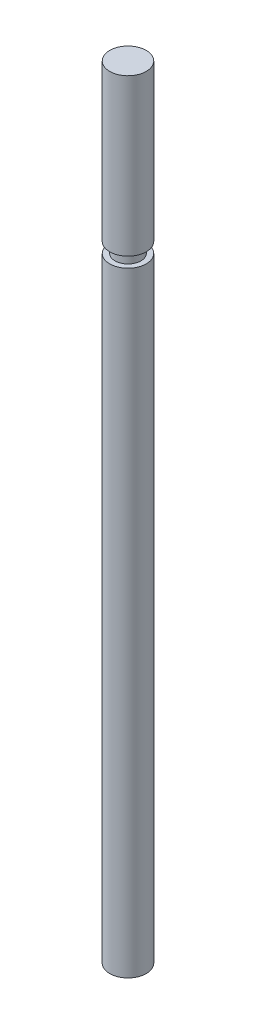
SolidWorks part; units mm, degrees
ref_plane "Front Plane" through (0, 0, 0) normal (0, 0, 1) x (1, 0, 0)
ref_plane "Top Plane" through (0, 0, 0) normal (0, 1, 0) x (1, 0, 0)
ref_plane "Right Plane" through (0, 0, 0) normal (1, 0, 0) x (0, 0, -1)
sketch "Sketch1" plane through (0, 0, 0) normal (0, 1, 0) x (1, 0, 0)
  circle A0 centre (0, 0) radius 1.75
  dimension "D1" = 3.5
extrude "Boss-Extrude1" add sketch "Sketch1" along normal blind 75
ref_plane "Plane1" through (0, 60, 0) normal (0, 1, 0) x (1, 0, 0)
sketch "Sketch2" plane through (0, 60, 0) normal (0, 1, 0) x (1, 0, 0)
  circle A0 centre (0, 0) radius 1.75 construction
  circle A1 centre (0, 0) radius 1.75
  circle A2 centre (0, 0) radius 1.25
  dimension "D1" = 0.5
extrude "Cut-Extrude1" cut sketch "Sketch2" against normal blind 1 contours A1 A2
